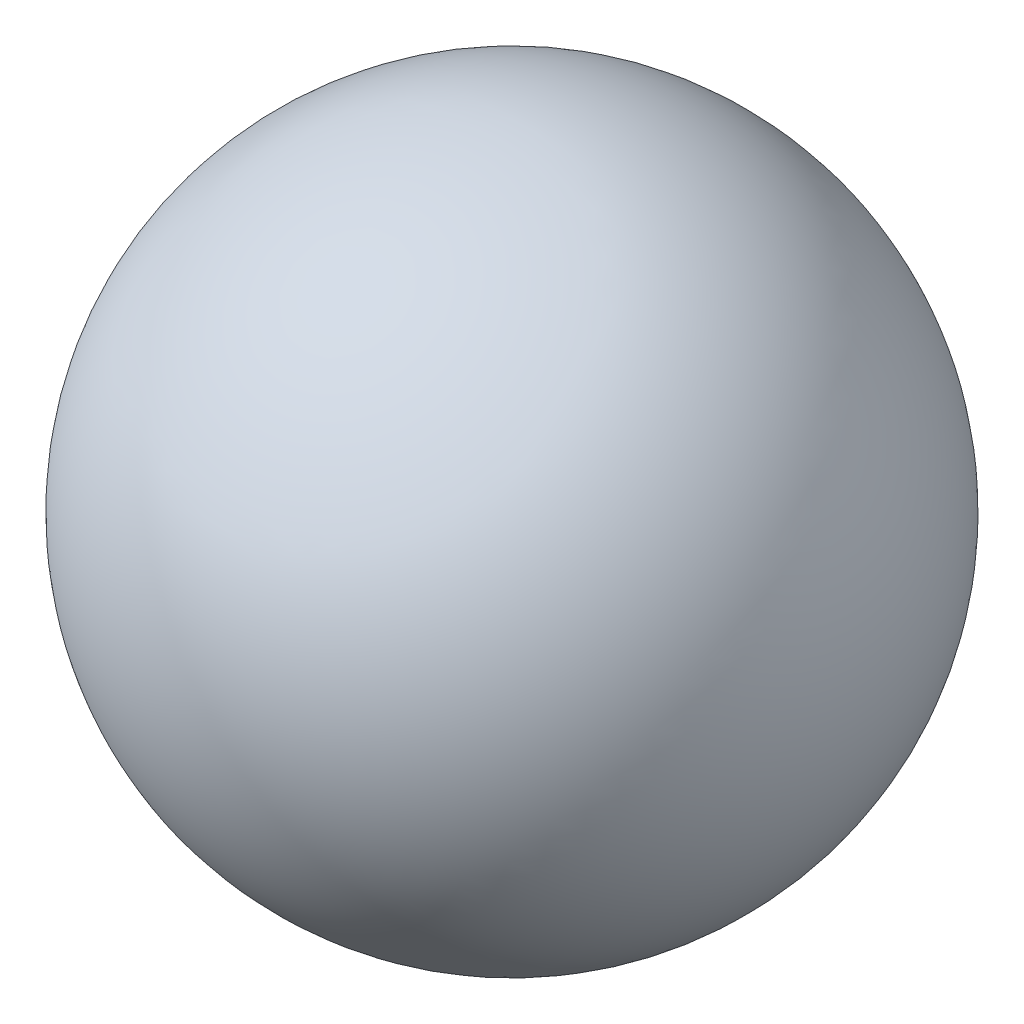
SolidWorks part; units mm, degrees
ref_plane "Front Plane" through (0, 0, 0) normal (0, 0, 1) x (1, 0, 0)
ref_plane "Top Plane" through (0, 0, 0) normal (0, 1, 0) x (1, 0, 0)
ref_plane "Right Plane" through (0, 0, 0) normal (1, 0, 0) x (0, 0, -1)
sketch "Sketch1" plane through (0, 0, 0) normal (0, 1, 0) x (1, 0, 0)
  line L0 (0, 11.43) -> (0, -11.43)
  line L1 (0, 11.43) -> (0, -11.43) construction
  arc A0 (0, -11.43) -> (0, 11.43) centre (0, 0) ccw
revolve "Revolve1" add sketch "Sketch1" angle 360 about L1
